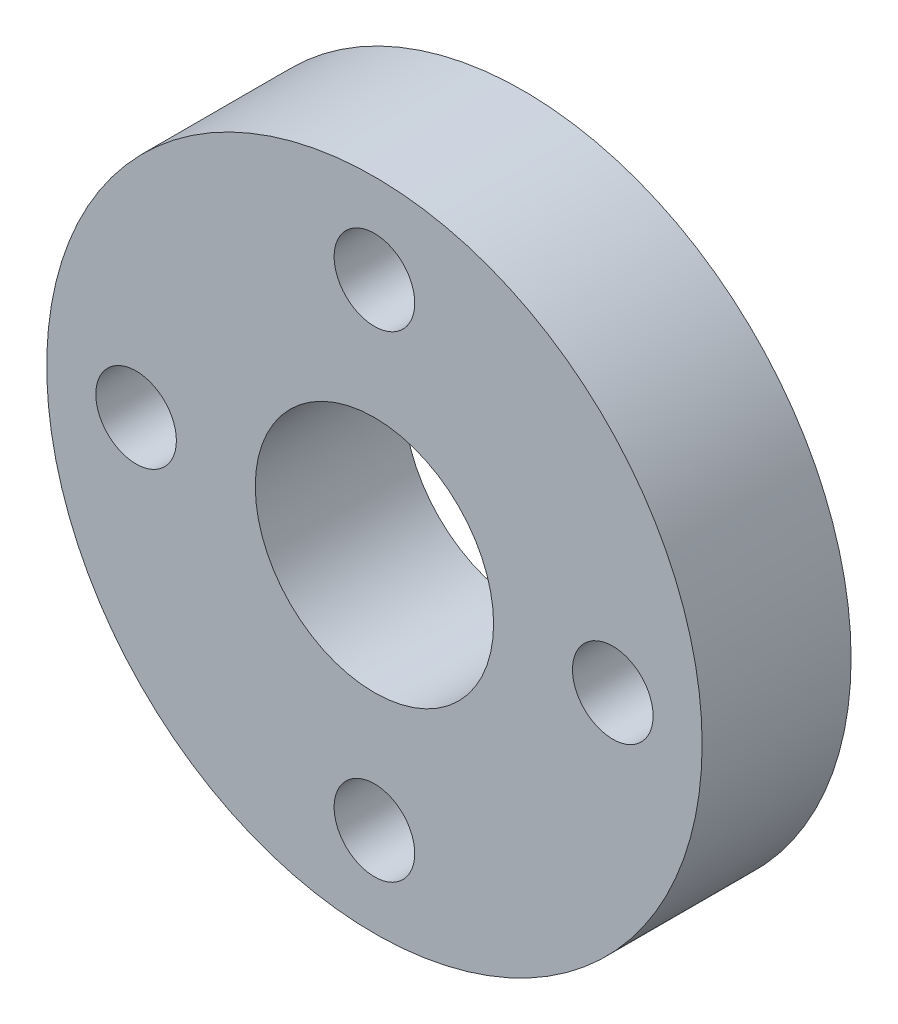
SolidWorks part; units mm, degrees
other "Defeature"
material "6061 Alloy"
ref_plane "Front Plane" through (0, 0, 0) normal (0, 0, 1) x (1, 0, 0)
ref_plane "Top Plane" through (0, 0, 0) normal (0, 1, 0) x (1, 0, 0)
ref_plane "Right Plane" through (0, 0, 0) normal (1, 0, 0) x (0, 0, -1)
sketch "Sketch1" plane through (0, 0, 0) normal (0, 0, 1) x (1, 0, 0)
  circle A0 centre (0, 0) radius 11
  circle A1 centre (0, 0) radius 4
  dimension "D1" = 22
  dimension "D2" = 8
extrude "Boss-Extrude1" add sketch "Sketch1" along normal mid plane 5
sketch "Sketch2" plane through (0, 0, 2.5) normal (0, 0, 1) x (1, 0, 0)
  circle A0 centre (0, 0) radius 8 construction
  point P12 (-8, 0)
  point P13 (0, 8)
  point P14 (8, 0)
  point P15 (0, -8)
  dimension "D1" = 16
hole_wizard "#6-32 Tapped Hole1" positions "Sketch4" profile "Sketch3" tap size "#6-32" standard "ANSI Inch" end condition through all
sketch "Sketch4" plane through (0, 0, 2.5) normal (0, 0, 1) x (1, 0, 0)
  point P0 (-8, 0)
  point P3 (0, -8)
  point P6 (8, 0)
  point P9 (0, 8)
sketch "Sketch3" plane through (-8, 0, 2.5) normal (1, 0, 0) x (0, -1, 0)
  line L0 (0, 0) -> (0, 5)
  line L1 (0, 5) -> (1.3525, 5)
  line L2 (1.3525, 5) -> (1.3525, 0)
  line L5 (1.3525, 0) -> (0, 0)
  line L11 (0, -6.35) -> (0, 107.95) construction
  dimension "Thru Tap Drill Dia." = 2.7051
  dimension "Thru Tap Drill Depth" = 5
cosmetic thread "Hole Thread1" parameters "D2"=3.5052
cosmetic thread "Hole Thread2" parameters "D2"=3.5052
cosmetic thread "Hole Thread3" parameters "D2"=3.5052
cosmetic thread "Hole Thread4" parameters "D2"=3.5052
